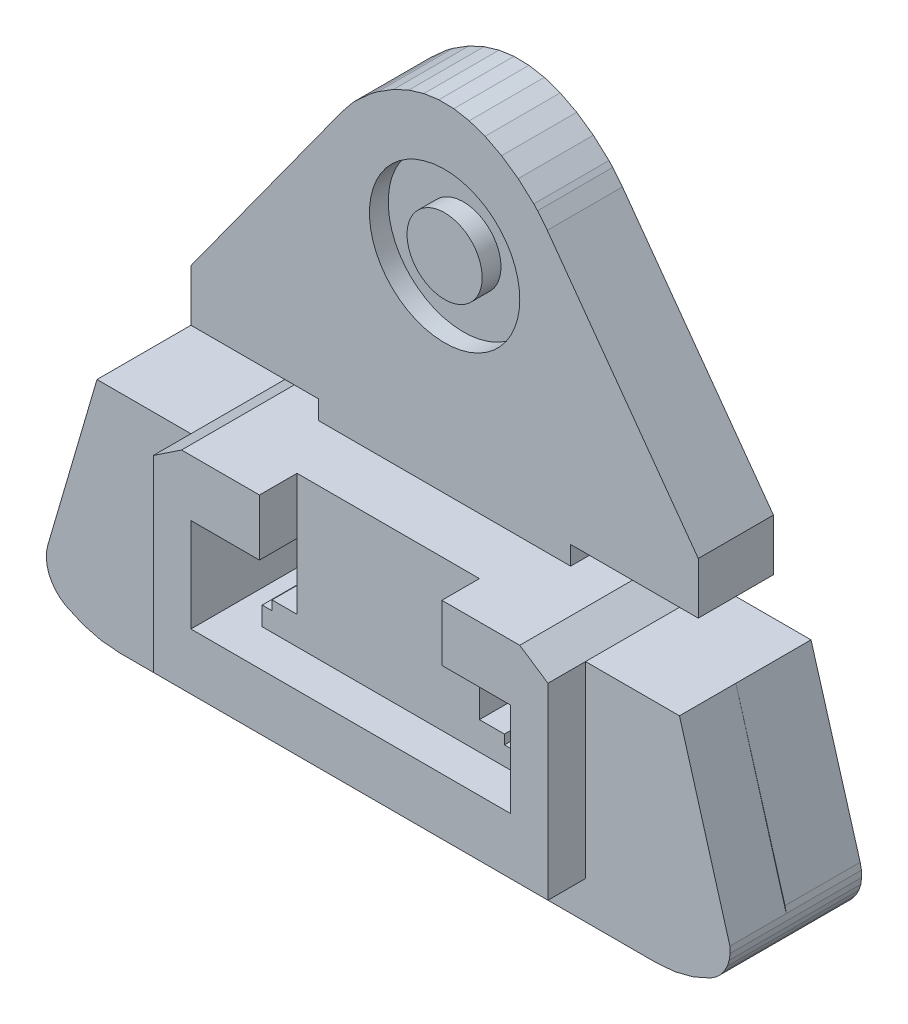
SolidWorks part; units mm, degrees
ref_plane "Front Plane" through (0, 0, 0) normal (0, 0, 1) x (1, 0, 0)
ref_plane "Top Plane" through (0, 0, 0) normal (0, 1, 0) x (1, 0, 0)
ref_plane "Right Plane" through (0, 0, 0) normal (1, 0, 0) x (0, 0, -1)
sketch "Sketch1" plane through (0, 0, 0) normal (0, 0, 1) x (1, 0, 0)
  line L0 (5.4649, 12.362) -> (13.5, 1.2547)
  line L1 (13.5, 1.2547) -> (13.5, -1.4953)
  line L2 (13.5, -1.4953) -> (6.7082, -1.4953)
  line L3 (6.7082, -1.4953) -> (6.7082, -2.4953)
  line L4 (6.7082, -2.4953) -> (9, -2.4953)
  line L5 (9, -2.4953) -> (10.5, -3.4953)
  line L6 (10.5, -3.4953) -> (15.5, -3.4953)
  line L7 (15.5, -3.4953) -> (18.1167, -12.4357)
  line L8 (5.4649, 12.362) -> (4.9475, 13.0047)
  line L9 (4.9475, 13.0047) -> (4.7468, 13.2211)
  line L10 (4.7468, 13.2211) -> (3.9157, 13.9715)
  line L11 (3.9157, 13.9715) -> (3.0305, 14.5863)
  line L12 (3.0305, 14.5863) -> (2.1524, 15.0414)
  line L13 (2.1524, 15.0414) -> (1.3079, 15.3336)
  line L14 (1.3079, 15.3336) -> (0.4893, 15.4808)
  line L15 (0.4893, 15.4808) -> (-0.3069, 15.4953)
  line L16 (-0.3069, 15.4953) -> (-1.1028, 15.3831)
  line L17 (-1.1028, 15.3831) -> (-1.9024, 15.1428)
  line L18 (-1.9024, 15.1428) -> (-2.7155, 14.7673)
  line L19 (-2.7155, 14.7673) -> (-3.5507, 14.2439)
  line L20 (-3.5507, 14.2439) -> (-3.9157, 13.9715)
  line L21 (-3.9157, 13.9715) -> (-4.7467, 13.2211)
  line L22 (-4.7467, 13.2211) -> (-4.9475, 13.0047)
  line L23 (-4.9475, 13.0047) -> (-5.4649, 12.362)
  line L24 (-5.4649, 12.362) -> (-13.5, 1.2547)
  line L25 (-13.5, 1.2547) -> (-13.5, -1.4953)
  line L26 (-13.5, -1.4953) -> (-6.7082, -1.4953)
  line L27 (-6.7082, -1.4953) -> (-6.7082, -2.4953)
  line L28 (-6.7082, -2.4953) -> (-9, -2.4953)
  line L29 (-9, -2.4953) -> (-10.5, -3.4953)
  line L30 (-10.5, -3.4953) -> (-15.5, -3.4953)
  line L31 (-15.5, -3.4953) -> (-18.1167, -12.4357)
  line L32 (-18.1167, -12.4357) -> (-18.1838, -12.7664)
  line L33 (-18.1838, -12.7664) -> (-18.1944, -13.1037)
  line L34 (-18.1944, -13.1037) -> (-18.1482, -13.4379)
  line L35 (-18.1482, -13.4379) -> (-18.0464, -13.7596)
  line L36 (-18.0464, -13.7596) -> (-17.8919, -14.0596)
  line L37 (-17.8919, -14.0596) -> (-17.6892, -14.3294)
  line L38 (-17.6892, -14.3294) -> (-17.4441, -14.5612)
  line L39 (-17.4441, -14.5612) -> (-17.1635, -14.7486)
  line L40 (-17.1635, -14.7486) -> (-16.2439, -15.1595)
  line L41 (-16.2439, -15.1595) -> (-15.2684, -15.4108)
  line L42 (-15.2684, -15.4108) -> (-14.2647, -15.4953)
  line L43 (-14.2647, -15.4953) -> (14.2647, -15.4953)
  line L44 (14.2647, -15.4953) -> (15.2685, -15.4108)
  line L45 (15.2685, -15.4108) -> (16.2439, -15.1595)
  line L46 (16.2439, -15.1595) -> (17.1635, -14.7486)
  line L47 (17.1635, -14.7486) -> (17.4441, -14.5612)
  line L48 (17.4441, -14.5612) -> (17.6892, -14.3294)
  line L49 (17.6892, -14.3294) -> (17.8919, -14.0596)
  line L50 (17.8919, -14.0596) -> (18.0464, -13.7596)
  line L51 (18.0464, -13.7596) -> (18.1482, -13.4379)
  line L52 (18.1482, -13.4379) -> (18.1944, -13.1037)
  line L53 (18.1944, -13.1037) -> (18.1838, -12.7664)
  line L54 (18.1838, -12.7664) -> (18.1167, -12.4357)
  line L55 (6.7082, -10.4953) -> (8.5, -10.4953)
  line L56 (8.5, -10.4953) -> (8.5, -5.4953)
  line L57 (8.5, -5.4953) -> (4.8542, -5.4953)
  line L58 (4.8542, -5.4953) -> (4.8542, -8.9953)
  line L59 (4.8542, -8.9953) -> (6.1847, -8.9953)
  line L60 (6.1847, -8.9953) -> (6.1847, -9.4953)
  line L61 (6.1847, -9.4953) -> (6.7082, -9.4953)
  line L62 (6.7082, -9.4953) -> (6.7082, -10.4953)
  line L63 (-4.8541, -5.4953) -> (-8.5, -5.4953)
  line L64 (-8.5, -5.4953) -> (-8.5, -10.4953)
  line L65 (-8.5, -10.4953) -> (-6.7082, -10.4953)
  line L66 (-6.7082, -10.4953) -> (-6.7082, -9.4953)
  line L67 (-6.7082, -9.4953) -> (-6.1847, -9.4953)
  line L68 (-6.1847, -9.4953) -> (-6.1847, -8.9953)
  line L69 (-6.1847, -8.9953) -> (-4.8541, -8.9953)
  line L70 (-4.8541, -8.9953) -> (-4.8541, -5.4953)
extrude "Boss-Extrude1" add sketch "Sketch1" along normal blind 4
sketch "Sketch4" plane through (0, 0, 4) normal (0, 0, 1) x (1, 0, 0)
  circle A0 centre (0, 8.4427) radius 4
  circle A1 centre (0, 8.4427) radius 2
extrude "Cut-Extrude1" cut sketch "Sketch4" against normal blind 1
sketch "Sketch7" plane through (0, 0, 4) normal (0, 0, 1) x (1, 0, 0)
  line L0 (-15.5, -3.4953) -> (-18.1167, -12.4357)
  line L1 (-18.1167, -12.4357) -> (-18.1503, -12.601)
  line L2 (-18.1167, -12.4357) -> (-18.1838, -12.7664) construction
  line L3 (-18.1503, -12.601) -> (-18.1838, -12.7664)
  line L4 (-18.1838, -12.7664) -> (-18.1891, -12.935)
  line L5 (-18.1838, -12.7664) -> (-18.1944, -13.1037) construction
  line L6 (-18.1891, -12.935) -> (-18.1944, -13.1037)
  line L7 (-18.1944, -13.1037) -> (-18.1713, -13.2708)
  line L8 (-18.1944, -13.1037) -> (-18.1482, -13.4379) construction
  line L9 (-18.1713, -13.2708) -> (-18.1482, -13.4379)
  line L10 (-18.1482, -13.4379) -> (-18.0464, -13.7596)
  line L11 (-18.0464, -13.7596) -> (-17.8919, -14.0596)
  line L12 (-17.8919, -14.0596) -> (-17.6892, -14.3294)
  line L13 (-17.6892, -14.3294) -> (-17.4441, -14.5612)
  line L14 (-17.4441, -14.5612) -> (-17.1635, -14.7486)
  line L15 (-17.1635, -14.7486) -> (-16.2439, -15.1595)
  line L16 (-16.2439, -15.1595) -> (-15.2684, -15.4108)
  line L17 (-15.2684, -15.4108) -> (-14.2647, -15.4953)
  line L18 (-14.2647, -15.4953) -> (14.2647, -15.4953)
  line L19 (14.2647, -15.4953) -> (15.2685, -15.4108)
  line L20 (15.2685, -15.4108) -> (16.2439, -15.1595)
  line L21 (16.2439, -15.1595) -> (17.1635, -14.7486)
  line L22 (17.1635, -14.7486) -> (17.4441, -14.5612)
  line L23 (17.4441, -14.5612) -> (17.6892, -14.3294)
  line L24 (17.6892, -14.3294) -> (17.8919, -14.0596)
  line L25 (17.8919, -14.0596) -> (18.0464, -13.7596)
  line L26 (18.0464, -13.7596) -> (18.1482, -13.4379)
  line L27 (18.1482, -13.4379) -> (18.1944, -13.1037)
  line L28 (18.1944, -13.1037) -> (18.1838, -12.7664)
  line L29 (18.1838, -12.7664) -> (15.5, -3.4953)
  line L30 (15.5, -3.4953) -> (10.5, -3.4953)
  line L31 (10.5, -3.4953) -> (9, -2.4953)
  line L32 (9, -2.4953) -> (6.7082, -2.4953)
  line L33 (-15.5, -3.4953) -> (-10.5, -3.4953)
  line L34 (-10.5, -3.4953) -> (-9, -2.4953)
  line L35 (-9, -2.4953) -> (-6.7082, -2.4953)
  line L36 (-6.7082, -2.4953) -> (6.7082, -2.4953)
  line L37 (-8.5, -5.4953) -> (-8.5, -10.4953)
  line L38 (-8.5, -10.4953) -> (-6.7082, -10.4953)
  line L39 (-6.7082, -10.4953) -> (-6.7082, -9.4953)
  line L40 (-6.7082, -9.4953) -> (-6.1847, -9.4953)
  line L41 (-6.1847, -9.4953) -> (-6.1847, -8.9953)
  line L42 (-6.1847, -8.9953) -> (-4.8541, -8.9953)
  line L43 (-4.8541, -8.9953) -> (-4.8541, -5.4953)
  line L44 (-4.8541, -5.4953) -> (-8.5, -5.4953)
  line L45 (4.8542, -5.4953) -> (8.5, -5.4953)
  line L46 (8.5, -5.4953) -> (8.5, -10.4953)
  line L47 (8.5, -10.4953) -> (6.7082, -10.4953)
  line L48 (6.7082, -10.4953) -> (6.7082, -9.4953)
  line L49 (6.7082, -9.4953) -> (6.1847, -9.4953)
  line L50 (6.1847, -9.4953) -> (6.1847, -8.9953)
  line L51 (6.1847, -8.9953) -> (4.8542, -8.9953)
  line L52 (4.8542, -8.9953) -> (4.8542, -5.4953)
extrude "Boss-Extrude2" add sketch "Sketch7" along normal blind 3
sketch "Sketch8" plane through (0, 0, 7) normal (0, 0, 1) x (1, 0, 0)
  line L0 (-9, -2.4953) -> (-10.5, -3.4953)
  line L1 (-10.5, -3.4953) -> (-10.5, -13.4965)
  line L2 (-9, -2.4953) -> (-6.7082, -2.4953)
  line L4 (6.7082, -2.4953) -> (9, -2.4953)
  line L5 (9, -2.4953) -> (10.5, -3.4953)
  line L6 (10.5, -3.4953) -> (10.5, -13.4965)
  line L8 (10.5, -13.4965) -> (-10.5, -13.4965)
  line L12 (-8.5, -10.4953) -> (8.5, -10.4953)
  line L17 (-8.5, -10.4953) -> (-8.5, -5.4953)
  line L18 (-8.5, -5.4953) -> (-4.8541, -5.4953)
  line L19 (-4.8541, -5.4953) -> (-4.8541, -2.4953)
  line L20 (9, -2.4953) -> (-9, -2.4953) construction
  line L21 (-4.8541, -2.4953) -> (-6.7082, -2.4953)
  line L22 (8.5, -10.4953) -> (8.5, -5.4953)
  line L23 (8.5, -5.4953) -> (4.8542, -5.4953)
  line L24 (4.8542, -5.4953) -> (4.8542, -2.4953)
  line L25 (4.8542, -2.4953) -> (9, -2.4953)
  line M27 (10.5, -3.4953) -> (9, -2.4953)
  line M28 (9, -2.4953) -> (-9, -2.4953)
  line M29 (-9, -2.4953) -> (-10.5, -3.4953)
  line M30 (-8.5, -10.4953) -> (-8.5, -5.4953)
  line M31 (-8.5, -5.4953) -> (-4.8541, -5.4953)
  line M37 (-6.7082, -10.4953) -> (-8.5, -10.4953)
  line M40 (4.8542, -5.4953) -> (8.5, -5.4953)
  line M41 (8.5, -5.4953) -> (8.5, -10.4953)
  line M42 (8.5, -10.4953) -> (6.7082, -10.4953)
extrude "Boss-Extrude3" add sketch "Sketch8" along normal blind 2 contours L24 L12 L19 L1 L8 L6 M40 M41 M42 M37 M30 M31 M28 M29 M27
sketch "Sketch9" plane through (0, 0, 0) normal (0, 0, -1) x (-1, 0, 0)
  line L1 (-5.3, 4.304) -> (5.3, 4.304)
  line L2 (-5.3, 4.304) -> (-5.3, 8.904)
  line L3 (-5.3, 8.904) -> (5.3, 8.904)
  line L4 (5.3, 4.304) -> (5.3, 8.904)
  line L5 (-5.3, 4.304) -> (5.3, 8.904) construction
  line L6 (-5.3, 8.904) -> (5.3, 4.304) construction
  point P0 (0, 6.604)
  point P5 (0, 0)
  dimension "D1" = 10.6
extrude "Cut-Extrude2" cut sketch "Sketch9" against normal blind 2
